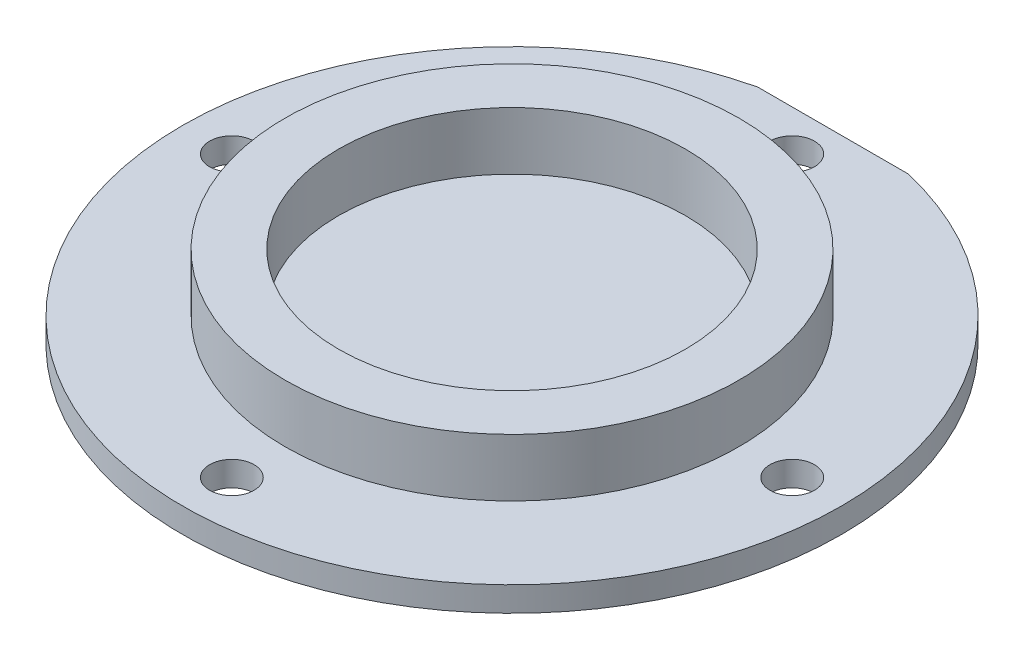
SolidWorks part; units mm, degrees
ref_plane "Front Plane" through (0, 0, 0) normal (0, 0, 1) x (1, 0, 0)
ref_plane "Top Plane" through (0, 0, 0) normal (0, 1, 0) x (1, 0, 0)
ref_plane "Right Plane" through (0, 0, 0) normal (1, 0, 0) x (0, 0, -1)
sketch "Sketch1" plane through (0, 0, 0) normal (0, 1, 0) x (1, 0, 0)
  line L0 (-9.1197, 38.9465) -> (9.1197, 38.9465)
  arc A0 (-9.1197, 38.9465) -> (9.1197, 38.9465) centre (0, 0) ccw
  circle A1 centre (0, 34.0074) radius 2.7
  circle A2 centre (0, 34.0074) radius 2.7 construction
  circle A3 centre (34.0074, 0) radius 2.7
  circle A5 centre (-34.0074, 0) radius 2.7
  circle A6 centre (0, -34.0074) radius 2.7 construction
  circle A7 centre (0, -34.0074) radius 2.7
  point P1 (0, 38.9465)
  dimension "D1" = 80
extrude "Boss-Extrude1" add sketch "Sketch1" along normal blind 3
sketch "Sketch2" plane through (0, 3, 0) normal (0, 1, 0) x (1, 0, 0)
  circle A0 centre (0, 0) radius 21.05
  circle A1 centre (0, 0) radius 27.55
  dimension "D1" = 42.1
  dimension "D2" = 6.5
extrude "Boss-Extrude2" add sketch "Sketch2" along normal blind 7
